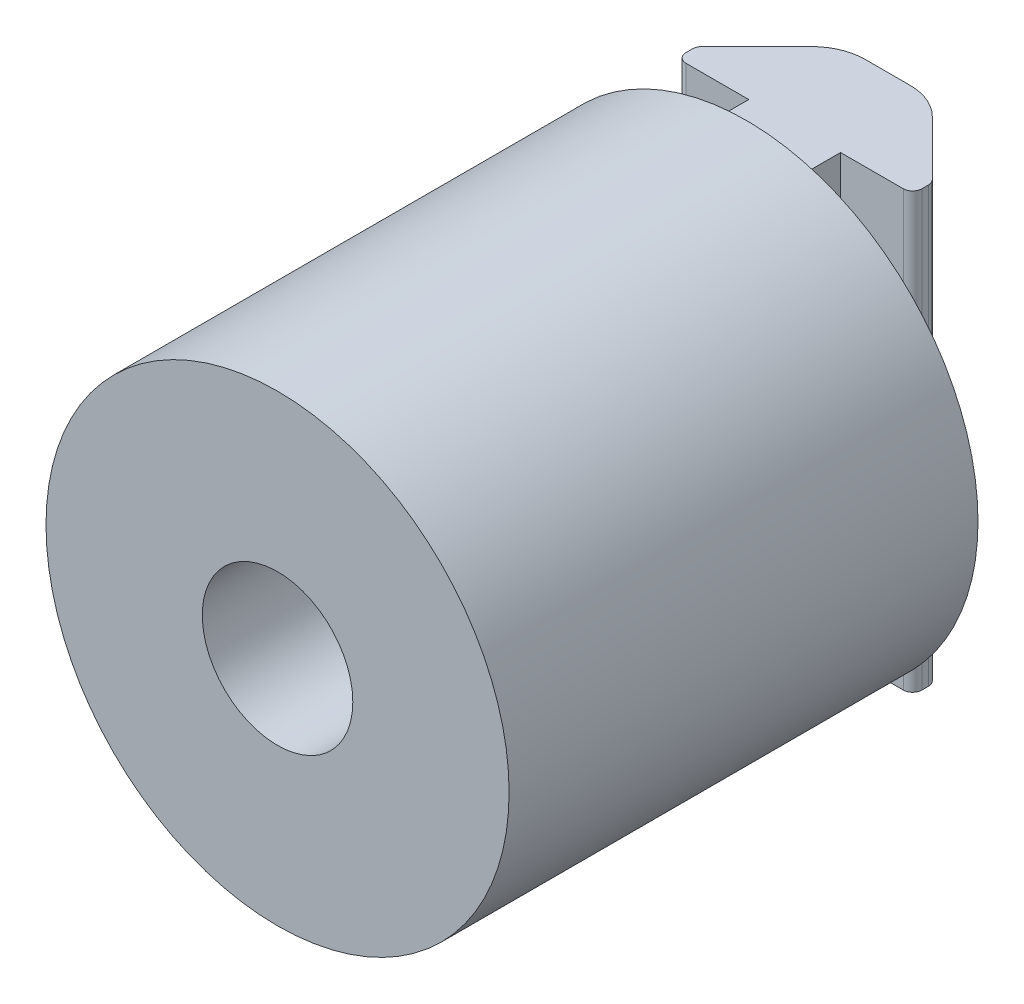
SolidWorks part; units mm, degrees
ref_plane "Front Plane" through (0, 0, 0) normal (0, 0, 1) x (1, 0, 0)
ref_plane "Top Plane" through (0, 0, 0) normal (0, 1, 0) x (1, 0, 0)
ref_plane "Right Plane" through (0, 0, 0) normal (1, 0, 0) x (0, 0, -1)
sketch "Sketch2" plane through (0, 0, 0) normal (0, 1, 0) x (1, 0, 0)
  line L104 (-14.3277, 0) -> (-9.4961, 0) construction
  line L105 (-7.9763, 0) -> (-5.6176, 0) construction
  line L106 (-4.064, 1.5536) -> (-4.064, 2.5104) construction
  line L107 (-5.6176, 4.064) -> (-9.3853, 4.064) construction
  line L108 (-10.287, 4.9657) -> (-10.287, 5.534) construction
  line L109 (-10.0229, 6.1716) -> (-5.2921, 10.9024) construction
  line L110 (-1.9335, 12.2936) -> (1.9335, 12.2936) construction
  line L111 (5.2921, 10.9024) -> (10.0229, 6.1716) construction
  line L112 (10.287, 5.534) -> (10.287, 4.9657) construction
  line L113 (9.3853, 4.064) -> (5.6176, 4.064) construction
  line L114 (4.064, 2.5104) -> (4.064, 1.5536) construction
  line L115 (5.6176, 0) -> (7.9763, 0) construction
  line L116 (9.4961, 0) -> (14.3277, 0) construction
  line L117 (19.05, 4.7223) -> (19.05, 9.5539) construction
  line L118 (19.05, 11.0737) -> (19.05, 13.4324) construction
  line L119 (17.4964, 14.986) -> (16.5396, 14.986) construction
  line L120 (14.986, 13.4324) -> (14.986, 9.6647) construction
  line L121 (14.0843, 8.763) -> (13.5524, 8.763) construction
  line L122 (12.9148, 9.0271) -> (8.144, 13.7978) construction
  line L123 (6.7564, 17.1478) -> (6.7564, 20.9522) construction
  line L124 (8.144, 24.3022) -> (12.9148, 29.0729) construction
  line L125 (13.5524, 29.337) -> (14.0843, 29.337) construction
  line L126 (14.986, 28.4353) -> (14.986, 24.6676) construction
  line L127 (16.5396, 23.114) -> (17.4964, 23.114) construction
  line L128 (19.05, 24.6676) -> (19.05, 27.0263) construction
  line L129 (19.05, 28.5461) -> (19.05, 33.3777) construction
  line L130 (14.3277, 38.1) -> (9.4961, 38.1) construction
  line L131 (7.9763, 38.1) -> (5.6176, 38.1) construction
  line L132 (4.064, 36.5464) -> (4.064, 35.5896) construction
  line L133 (5.6176, 34.036) -> (9.3853, 34.036) construction
  line L134 (10.287, 33.1343) -> (10.287, 32.566) construction
  line L135 (10.0229, 31.9284) -> (5.2921, 27.1976) construction
  line L136 (1.9335, 25.8064) -> (-1.9335, 25.8064) construction
  line L137 (-5.2921, 27.1976) -> (-10.0229, 31.9284) construction
  line L138 (-10.287, 32.566) -> (-10.287, 33.1343) construction
  line L139 (-9.3853, 34.036) -> (-5.6176, 34.036) construction
  line L140 (-4.064, 35.5896) -> (-4.064, 36.5464) construction
  line L141 (-5.6176, 38.1) -> (-7.9763, 38.1) construction
  line L142 (-9.4961, 38.1) -> (-14.3277, 38.1) construction
  line L143 (-19.05, 33.3777) -> (-19.05, 28.5482) construction
  line L144 (-19.05, 27.0242) -> (-19.05, 24.6676) construction
  line L145 (-17.4964, 23.114) -> (-16.5396, 23.114) construction
  line L146 (-14.986, 24.6676) -> (-14.986, 28.4353) construction
  line L147 (-14.0843, 29.337) -> (-13.5524, 29.337) construction
  line L148 (-12.9148, 29.0729) -> (-8.144, 24.3022) construction
  line L149 (-6.7564, 20.9522) -> (-6.7564, 17.1478) construction
  line L150 (-8.144, 13.7978) -> (-12.9148, 9.0271) construction
  line L151 (-13.5524, 8.763) -> (-14.0843, 8.763) construction
  line L152 (-14.986, 9.6647) -> (-14.986, 13.4324) construction
  line L153 (-16.5396, 14.986) -> (-17.4964, 14.986) construction
  line L154 (-19.05, 13.4324) -> (-19.05, 11.0758) construction
  line L155 (-19.05, 9.5518) -> (-19.05, 4.7223) construction
  arc A120 (-19.05, 3.2025) -> (-19.05, 4.7223) centre (-18.9933, 3.9624) ccw construction
  arc A121 (-19.05, 3.2025) -> (-15.8475, 0) centre (-15.8751, 3.1749) ccw construction
  arc A122 (-14.3277, 0) -> (-15.8475, 0) centre (-15.0876, 0.0567) ccw construction
  arc A123 (-7.9763, 0) -> (-9.4961, 0) centre (-8.7362, 0.0567) ccw construction
  arc A124 (-5.6176, 0) -> (-4.064, 1.5536) centre (-5.6176, 1.5536) ccw construction
  arc A125 (-4.064, 2.5104) -> (-5.6176, 4.064) centre (-5.6176, 2.5104) ccw construction
  arc A126 (-10.287, 4.9657) -> (-9.3853, 4.064) centre (-9.3853, 4.9657) ccw construction
  arc A127 (-10.0229, 6.1716) -> (-10.287, 5.534) centre (-9.3853, 5.534) ccw construction
  arc A128 (-1.9335, 12.2936) -> (-5.2921, 10.9024) centre (-1.9335, 7.5438) ccw construction
  arc A129 (5.2921, 10.9024) -> (1.9335, 12.2936) centre (1.9335, 7.5438) ccw construction
  arc A130 (10.287, 5.534) -> (10.0229, 6.1716) centre (9.3853, 5.534) ccw construction
  arc A131 (9.3853, 4.064) -> (10.287, 4.9657) centre (9.3853, 4.9657) ccw construction
  arc A132 (5.6176, 4.064) -> (4.064, 2.5104) centre (5.6176, 2.5104) ccw construction
  arc A133 (4.064, 1.5536) -> (5.6176, 0) centre (5.6176, 1.5536) ccw construction
  arc A134 (9.4961, 0) -> (7.9763, 0) centre (8.7362, 0.0567) ccw construction
  arc A135 (15.8475, 0) -> (14.3277, 0) centre (15.0876, 0.0567) ccw construction
  arc A136 (15.8475, 0) -> (19.05, 3.2025) centre (15.8751, 3.1749) ccw construction
  arc A137 (19.05, 4.7223) -> (19.05, 3.2025) centre (18.9933, 3.9624) ccw construction
  arc A138 (19.05, 11.0737) -> (19.05, 9.5539) centre (18.9933, 10.3138) ccw construction
  arc A139 (19.05, 13.4324) -> (17.4964, 14.986) centre (17.4964, 13.4324) ccw construction
  arc A140 (16.5396, 14.986) -> (14.986, 13.4324) centre (16.5396, 13.4324) ccw construction
  arc A141 (14.0843, 8.763) -> (14.986, 9.6647) centre (14.0843, 9.6647) ccw construction
  arc A142 (12.9148, 9.0271) -> (13.5524, 8.763) centre (13.5524, 9.6647) ccw construction
  arc A143 (6.7564, 17.1478) -> (8.144, 13.7978) centre (11.494, 17.1478) ccw construction
  arc A144 (8.144, 24.3022) -> (6.7564, 20.9522) centre (11.494, 20.9522) ccw construction
  arc A145 (13.5524, 29.337) -> (12.9148, 29.0729) centre (13.5524, 28.4353) ccw construction
  arc A146 (14.986, 28.4353) -> (14.0843, 29.337) centre (14.0843, 28.4353) ccw construction
  arc A147 (14.986, 24.6676) -> (16.5396, 23.114) centre (16.5396, 24.6676) ccw construction
  arc A148 (17.4964, 23.114) -> (19.05, 24.6676) centre (17.4964, 24.6676) ccw construction
  arc A149 (19.05, 28.5461) -> (19.05, 27.0263) centre (18.9933, 27.7862) ccw construction
  arc A150 (19.05, 34.8975) -> (19.05, 33.3777) centre (18.9933, 34.1376) ccw construction
  arc A151 (19.05, 34.8975) -> (15.8475, 38.1) centre (15.8751, 34.9251) ccw construction
  arc A152 (14.3277, 38.1) -> (15.8475, 38.1) centre (15.0876, 38.0433) ccw construction
  arc A153 (7.9763, 38.1) -> (9.4961, 38.1) centre (8.7362, 38.0433) ccw construction
  arc A154 (5.6176, 38.1) -> (4.064, 36.5464) centre (5.6176, 36.5464) ccw construction
  arc A155 (4.064, 35.5896) -> (5.6176, 34.036) centre (5.6176, 35.5896) ccw construction
  arc A156 (10.287, 33.1343) -> (9.3853, 34.036) centre (9.3853, 33.1343) ccw construction
  arc A157 (10.0229, 31.9284) -> (10.287, 32.566) centre (9.3853, 32.566) ccw construction
  arc A158 (1.9335, 25.8064) -> (5.2921, 27.1976) centre (1.9335, 30.5562) ccw construction
  arc A159 (-5.2921, 27.1976) -> (-1.9335, 25.8064) centre (-1.9335, 30.5562) ccw construction
  arc A160 (-10.287, 32.566) -> (-10.0229, 31.9284) centre (-9.3853, 32.566) ccw construction
  arc A161 (-9.3853, 34.036) -> (-10.287, 33.1343) centre (-9.3853, 33.1343) ccw construction
  arc A162 (-5.6176, 34.036) -> (-4.064, 35.5896) centre (-5.6176, 35.5896) ccw construction
  arc A163 (-4.064, 36.5464) -> (-5.6176, 38.1) centre (-5.6176, 36.5464) ccw construction
  arc A164 (-9.4961, 38.1) -> (-7.9763, 38.1) centre (-8.7362, 38.0433) ccw construction
  arc A165 (-15.8475, 38.1) -> (-14.3277, 38.1) centre (-15.0876, 38.0433) ccw construction
  arc A166 (-15.8475, 38.1) -> (-19.05, 34.8975) centre (-15.8751, 34.9251) ccw construction
  arc A167 (-19.05, 33.3777) -> (-19.05, 34.8975) centre (-18.9933, 34.1376) ccw construction
  arc A168 (-19.05, 27.0242) -> (-19.05, 28.5482) centre (-19.05, 27.7862) ccw construction
  arc A169 (-19.05, 24.6676) -> (-17.4964, 23.114) centre (-17.4964, 24.6676) ccw construction
  arc A170 (-16.5396, 23.114) -> (-14.986, 24.6676) centre (-16.5396, 24.6676) ccw construction
  arc A171 (-14.0843, 29.337) -> (-14.986, 28.4353) centre (-14.0843, 28.4353) ccw construction
  arc A172 (-12.9148, 29.0729) -> (-13.5524, 29.337) centre (-13.5524, 28.4353) ccw construction
  arc A173 (-6.7564, 20.9522) -> (-8.144, 24.3022) centre (-11.494, 20.9522) ccw construction
  arc A174 (-8.144, 13.7978) -> (-6.7564, 17.1478) centre (-11.494, 17.1478) ccw construction
  arc A175 (-13.5524, 8.763) -> (-12.9148, 9.0271) centre (-13.5524, 9.6647) ccw construction
  arc A176 (-14.986, 9.6647) -> (-14.0843, 8.763) centre (-14.0843, 9.6647) ccw construction
  arc A177 (-14.986, 13.4324) -> (-16.5396, 14.986) centre (-16.5396, 13.4324) ccw construction
  arc A178 (-17.4964, 14.986) -> (-19.05, 13.4324) centre (-17.4964, 13.4324) ccw construction
  arc A179 (-19.05, 9.5518) -> (-19.05, 11.0758) centre (-19.05, 10.3138) ccw construction
sketch "Sketch3" plane through (0, 0, 0) normal (0, 1, 0) x (1, 0, 0)
  line L0 (-4.064, 1.5536) -> (-4.064, 2.5104) construction
  line L1 (-5.6176, 4.164) -> (-3.964, 4.164)
  line L2 (-3.964, 4.164) -> (-3.964, 2.5104)
  line L3 (4.064, 2.5104) -> (4.064, 1.5536) construction
  line L4 (-3.964, 1.5536) -> (-3.964, -0.1)
  line L5 (-3.964, -0.1) -> (3.964, -0.1)
  line L6 (3.964, -0.1) -> (3.964, 1.5536)
  line L7 (3.964, 2.5104) -> (3.964, 4.164)
  line L9 (3.964, 4.164) -> (5.6176, 4.164)
  line L10 (5.6176, 0) -> (7.9763, 0) construction
  line L12 (4.064, 2.5104) -> (4.064, 1.5536)
  line L13 (-4.064, 1.5536) -> (-4.064, 2.5104)
  line L14 (9.3853, 4.164) -> (5.6176, 4.164)
  line L15 (10.187, 5.534) -> (10.187, 4.9657)
  line L16 (5.2214, 10.8317) -> (9.9522, 6.1008)
  line L17 (-1.9335, 12.1936) -> (1.9335, 12.1936)
  line L18 (-9.9522, 6.1008) -> (-5.2214, 10.8317)
  line L19 (-10.187, 4.9657) -> (-10.187, 5.534)
  line L20 (-5.6176, 4.164) -> (-9.3853, 4.164)
  line L21 (9.3853, 4.164) -> (5.6176, 4.164)
  line L22 (10.187, 5.534) -> (10.187, 4.9657)
  line L23 (5.2214, 10.8317) -> (9.9522, 6.1008)
  line L24 (-1.9335, 12.1936) -> (1.9335, 12.1936)
  line L25 (-9.9522, 6.1008) -> (-5.2214, 10.8317)
  line L26 (-10.187, 4.9657) -> (-10.187, 5.534)
  line L27 (-5.6176, 4.164) -> (-9.3853, 4.164)
  line L28 (-3.964, 1.5536) -> (-3.964, 2.5104)
  line L29 (3.964, 2.5104) -> (3.964, 1.5536)
  arc A0 (-4.064, 2.5104) -> (-5.6176, 4.064) centre (-5.6176, 2.5104) ccw construction
  arc A2 (-5.6176, 0) -> (-4.064, 1.5536) centre (-5.6176, 1.5536) ccw construction
  arc A4 (4.064, 1.5536) -> (5.6176, 0) centre (5.6176, 1.5536) ccw construction
  arc A10 (5.6176, 4.064) -> (4.064, 2.5104) centre (5.6176, 2.5104) ccw construction
  arc A12 (9.3853, 4.164) -> (10.187, 4.9657) centre (9.3853, 4.9657) ccw
  arc A13 (10.187, 5.534) -> (9.9522, 6.1008) centre (9.3853, 5.534) ccw
  arc A14 (5.2214, 10.8317) -> (1.9335, 12.1936) centre (1.9335, 7.5438) ccw
  arc A15 (-1.9335, 12.1936) -> (-5.2214, 10.8317) centre (-1.9335, 7.5438) ccw
  arc A16 (-9.9522, 6.1008) -> (-10.187, 5.534) centre (-9.3853, 5.534) ccw
  arc A17 (-10.187, 4.9657) -> (-9.3853, 4.164) centre (-9.3853, 4.9657) ccw
  arc A18 (9.3853, 4.164) -> (10.187, 4.9657) centre (9.3853, 4.9657) ccw
  arc A19 (10.187, 5.534) -> (9.9522, 6.1008) centre (9.3853, 5.534) ccw
  arc A20 (5.2214, 10.8317) -> (1.9335, 12.1936) centre (1.9335, 7.5438) ccw
  arc A21 (-1.9335, 12.1936) -> (-5.2214, 10.8317) centre (-1.9335, 7.5438) ccw
  arc A22 (-9.9522, 6.1008) -> (-10.187, 5.534) centre (-9.3853, 5.534) ccw
  arc A23 (-10.187, 4.9657) -> (-9.3853, 4.164) centre (-9.3853, 4.9657) ccw
  arc A34 (5.6176, 4.064) -> (4.064, 2.5104) centre (5.6176, 2.5104) ccw
  arc A35 (4.064, 1.5536) -> (5.6176, 0) centre (5.6176, 1.5536) ccw
  arc A36 (-5.6176, 0) -> (-4.064, 1.5536) centre (-5.6176, 1.5536) ccw
  arc A37 (-4.064, 2.5104) -> (-5.6176, 4.064) centre (-5.6176, 2.5104) ccw
  arc A42 (-5.6176, -0.1) -> (-3.964, 1.5536) centre (-5.6176, 1.5536) ccw construction
  arc A43 (-3.964, 2.5104) -> (-5.6176, 4.164) centre (-5.6176, 2.5104) ccw construction
  arc A44 (5.6176, 4.164) -> (3.964, 2.5104) centre (5.6176, 2.5104) ccw construction
  arc A45 (3.964, 1.5536) -> (5.6176, -0.1) centre (5.6176, 1.5536) ccw construction
  dimension "D3" = 0.1
  dimension "D1" = 0.1
  dimension "D2" = 0.1
extrude "Boss-Extrude1" add sketch "Sketch3" along normal blind 17.5 and the other way blind 20
ref_plane "Plane1" through (0, 0, 5) normal (0, 0, 1) x (1, 0, 0)
sketch "Sketch4" plane through (0, 0, 5) normal (0, 0, 1) x (1, 0, 0)
  circle A0 centre (0, 0) radius 12.5
  circle A1 centre (0, 0) radius 7
  circle A2 centre (0, 0) radius 20
  dimension "D1" = 25
  dimension "D2" = 14
  dimension "D3" = 7.5
extrude "Boss-Extrude2" add sketch "Sketch4" along normal blind 5 and the other way blind 5 contours A2
sketch "Sketch5" plane through (0, 0, 10) normal (0, 0, 1) x (1, 0, 0)
  circle A0 centre (0, 0) radius 20 construction
  circle A1 centre (0, 0) radius 20
  circle A2 centre (0, 0) radius 12.5
  dimension "D1" = 7.5
extrude "Boss-Extrude3" add sketch "Sketch5" along normal blind 10.5
sketch "Sketch6" plane through (0, 0, 20.5) normal (0, 0, 1) x (1, 0, 0)
  circle A0 centre (0, 0) radius 6.5
  circle A1 centre (0, 0) radius 20 construction
  circle A2 centre (0, 0) radius 20
  dimension "D1" = 13
extrude "Boss-Extrude4" add sketch "Sketch6" along normal blind 20
ref_plane "Plane2" through (0, 20, 0) normal (0, 1, 0) x (1, 0, 0)
equation "\"D1@Sketch3\"=\"D2@Sketch3\""
equation "\"D3@Sketch3\"=\"D2@Sketch3\""
